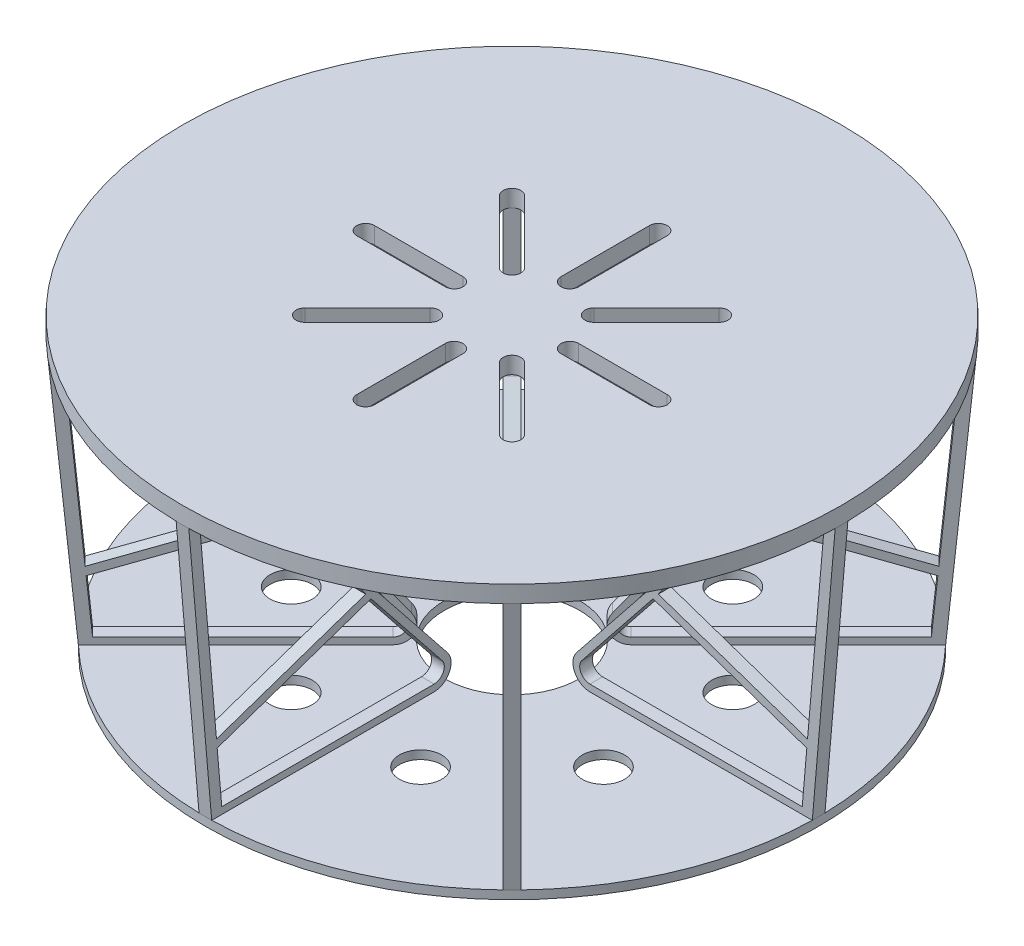
SolidWorks part; units mm, degrees
ref_plane "前视基准面" through (0, 0, 0) normal (0, 0, 1) x (1, 0, 0)
ref_plane "上视基准面" through (0, 0, 0) normal (0, 1, 0) x (1, 0, 0)
ref_plane "右视基准面" through (0, 0, 0) normal (1, 0, 0) x (0, 0, -1)
sketch "草图1" plane through (0, 0, 0) normal (0, 1, 0) x (1, 0, 0)
  circle A0 centre (0, 0) radius 362.93
  circle A1 centre (0, 0) radius 80
  dimension "D1" = 725.86
  dimension "D2" = 160
extrude "凸台-拉伸1" add sketch "草图1" along normal blind 10
ref_plane "基准面1" through (0, 322.6, 0) normal (0, 1, 0) x (1, 0, 0)
sketch "草图2" plane through (0, 322.6, 0) normal (0, 1, 0) x (1, 0, 0)
  circle A0 centre (0, 0) radius 390
  dimension "D1" = 780
extrude "凸台-拉伸2" add sketch "草图2" along normal blind 20 separate body
sketch "草图3" plane through (0, 10, 0) normal (0, 1, 0) x (1, 0, 0)
  line L0 (0, -200) -> (0, 0) construction
  circle A0 centre (0, 0) radius 200 construction
  circle A1 centre (76.5367, -184.7759) radius 25
  circle A2 centre (-76.5367, -184.7759) radius 25
  circle A3 centre (-184.7759, -76.5367) radius 25
  circle A4 centre (-184.7759, 76.5367) radius 25
  circle A5 centre (-76.5367, 184.7759) radius 25
  circle A6 centre (76.5367, 184.7759) radius 25
  circle A7 centre (184.7759, 76.5367) radius 25
  circle A8 centre (184.7759, -76.5367) radius 25
  dimension "D1" = 400
  dimension "D2" = 50
  dimension "D3" = 8
extrude "切除-拉伸1" cut sketch "草图3" against normal up to next (10 mm away)
sketch "草图4" plane through (0, 342.6, 0) normal (0, 1, 0) x (1, 0, 0)
  line L0 (0, -68.51) -> (0, -173.27) construction
  line L1 (10.47, -68.51) -> (10.47, -173.27)
  line L2 (-10.47, -68.51) -> (-10.47, -173.27)
  line L3 (-48.4439, -48.4439) -> (-122.5204, -122.5204) construction
  line L4 (-41.0405, -55.8473) -> (-115.117, -129.9238)
  line L5 (-55.8473, -41.0405) -> (-129.9238, -115.117)
  line L6 (-68.51, 0) -> (-173.27, 0) construction
  line L7 (-68.51, -10.47) -> (-173.27, -10.47)
  line L8 (-68.51, 10.47) -> (-173.27, 10.47)
  line L9 (-48.4439, 48.4439) -> (-122.5204, 122.5204) construction
  line L10 (-55.8473, 41.0405) -> (-129.9238, 115.117)
  line L11 (-41.0405, 55.8473) -> (-115.117, 129.9238)
  line L12 (0, 68.51) -> (0, 173.27) construction
  line L13 (-10.47, 68.51) -> (-10.47, 173.27)
  line L14 (10.47, 68.51) -> (10.47, 173.27)
  line L15 (48.4439, 48.4439) -> (122.5204, 122.5204) construction
  line L16 (41.0405, 55.8473) -> (115.117, 129.9238)
  line L17 (55.8473, 41.0405) -> (129.9238, 115.117)
  line L18 (68.51, 0) -> (173.27, 0) construction
  line L19 (68.51, 10.47) -> (173.27, 10.47)
  line L20 (68.51, -10.47) -> (173.27, -10.47)
  line L21 (48.4439, -48.4439) -> (122.5204, -122.5204) construction
  line L22 (55.8473, -41.0405) -> (129.9238, -115.117)
  line L23 (41.0405, -55.8473) -> (115.117, -129.9238)
  line L24 (0, 0) -> (0, -68.51) construction
  arc A0 (10.47, -68.51) -> (-10.47, -68.51) centre (0, -68.51) ccw
  arc A1 (-10.47, -173.27) -> (10.47, -173.27) centre (0, -173.27) ccw
  circle A2 centre (0, 0) radius 390 construction
  arc A3 (-41.0405, -55.8473) -> (-55.8473, -41.0405) centre (-48.4439, -48.4439) ccw
  arc A4 (-129.9238, -115.117) -> (-115.117, -129.9238) centre (-122.5204, -122.5204) ccw
  arc A5 (-68.51, -10.47) -> (-68.51, 10.47) centre (-68.51, 0) ccw
  arc A6 (-173.27, 10.47) -> (-173.27, -10.47) centre (-173.27, 0) ccw
  arc A7 (-55.8473, 41.0405) -> (-41.0405, 55.8473) centre (-48.4439, 48.4439) ccw
  arc A8 (-115.117, 129.9238) -> (-129.9238, 115.117) centre (-122.5204, 122.5204) ccw
  arc A9 (-10.47, 68.51) -> (10.47, 68.51) centre (0, 68.51) ccw
  arc A10 (10.47, 173.27) -> (-10.47, 173.27) centre (0, 173.27) ccw
  arc A11 (41.0405, 55.8473) -> (55.8473, 41.0405) centre (48.4439, 48.4439) ccw
  arc A12 (129.9238, 115.117) -> (115.117, 129.9238) centre (122.5204, 122.5204) ccw
  arc A13 (68.51, 10.47) -> (68.51, -10.47) centre (68.51, 0) ccw
  arc A14 (173.27, -10.47) -> (173.27, 10.47) centre (173.27, 0) ccw
  arc A15 (55.8473, -41.0405) -> (41.0405, -55.8473) centre (48.4439, -48.4439) ccw
  arc A16 (115.117, -129.9238) -> (129.9238, -115.117) centre (122.5204, -122.5204) ccw
  point P3 (0, -120.89)
  point P12 (0, 0)
  point P15 (-85.4821, -85.4821)
  point P22 (-120.89, 0)
  point P29 (-85.4821, 85.4821)
  point P36 (0, 120.89)
  point P43 (85.4821, 85.4821)
  point P50 (120.89, 0)
  point P57 (85.4821, -85.4821)
  dimension "D1" = 10.47
  dimension "D3" = 68.51
  dimension "D2" = 173.27
  dimension "D4" = 8
extrude "切除-拉伸2" cut sketch "草图4" against normal up to next (20 mm away)
sketch "草图5" plane through (0, 0, 0) normal (1, 0, 0) x (0, 0, -1)
  line L0 (-99.6207, 10) -> (-362.93, 10)
  line L1 (-362.93, 10) -> (-390, 322.6)
  line L2 (-390, 322.6) -> (-377.3729, 322.6)
  line L3 (-377.3729, 322.6) -> (-357.2713, 90.47)
  line L4 (-350.9957, 18) -> (-99.6207, 18)
  line L5 (-191.7329, 322.6) -> (-183.7329, 322.6)
  line L6 (-191.7329, 322.6) -> (-191.7329, 181.39)
  line L7 (-174.4185, 142.8942) -> (-90.2438, 37.4882)
  line L8 (-183.7329, 322.6) -> (-183.7329, 181.39)
  line L9 (-174.9894, 156.4294) -> (-83.9925, 42.4803)
  line L10 (-357.2713, 90.47) -> (-180.6627, 150.7275)
  line L11 (-174.4185, 142.8942) -> (-356.4333, 80.7922)
  line L12 (-356.4333, 80.7922) -> (-350.9957, 18)
  arc A0 (-191.7329, 181.39) -> (-180.6627, 150.7275) centre (-143.7329, 181.39) ccw
  arc A1 (-90.2438, 37.4882) -> (-99.6207, 18) centre (-99.6207, 30) cw
  arc A2 (-183.7329, 181.39) -> (-174.9894, 156.4294) centre (-143.7329, 181.39) ccw
  arc A3 (-83.9925, 42.4803) -> (-99.6207, 10) centre (-99.6207, 30) cw
  point P23 (-181.2407, 148.5877)
  point P24 (-358.9236, 109.5504)
  point P26 (0, 0)
  dimension "D2" = 48
  dimension "D5" = 40
  dimension "D9" = 12
  dimension "D10" = 20
  dimension "D1" = 141.21
  dimension "D3" = 12.58
  dimension "D4" = 8
  dimension "D6" = 8
  dimension "D7" = 185.64
  dimension "D8" = 141.39
  dimension "D11" = 76.11
  dimension "D12" = 9.43
  dimension "D13" = 232.13
extrude "凸台-拉伸3" add sketch "草图5" along normal mid plane 15
pattern_circular "阵列(圆周)1" count 8 over 360 about axis through (0, 0, 0) along (0, 1, 0) of "凸台-拉伸3"
